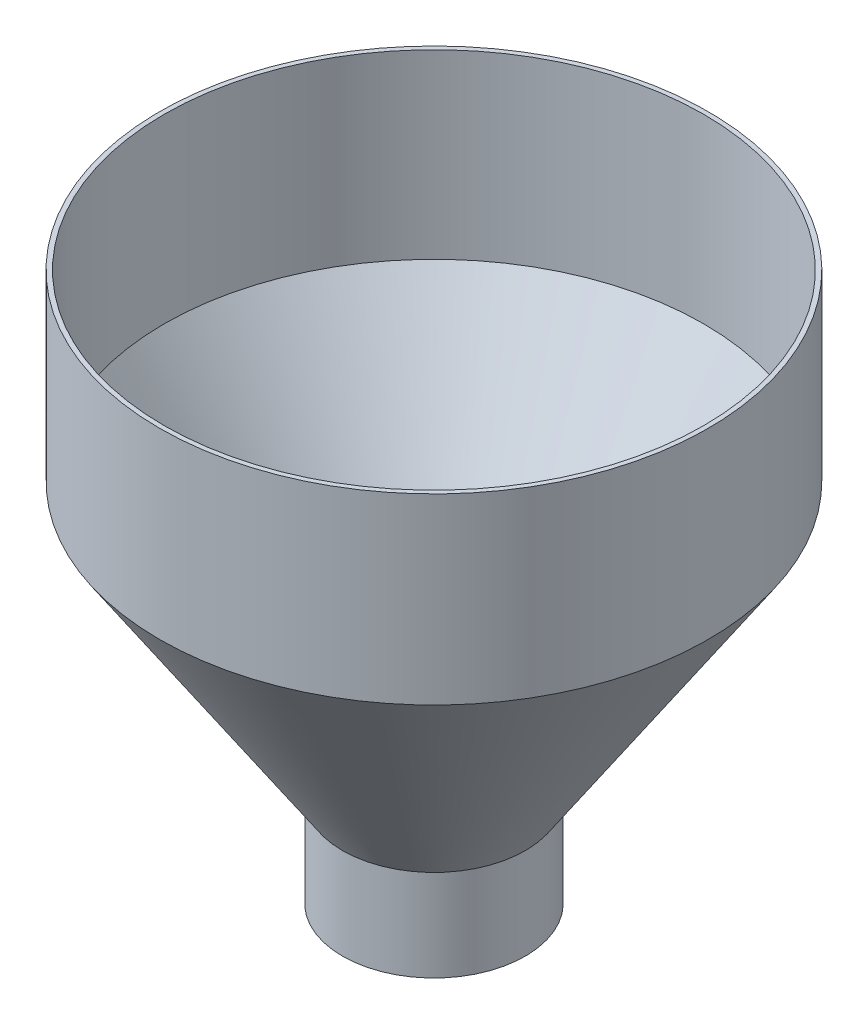
SolidWorks part; units mm, degrees
ref_plane "Front Plane" through (0, 0, 0) normal (0, 0, 1) x (1, 0, 0)
ref_plane "Top Plane" through (0, 0, 0) normal (0, 1, 0) x (1, 0, 0)
ref_plane "Right Plane" through (0, 0, 0) normal (1, 0, 0) x (0, 0, -1)
sketch "Sketch1" plane through (0, 0, 0) normal (0, 0, 1) x (1, 0, 0)
  line L0 (-120, 160) -> (-40, 40)
  line L1 (0, 0) -> (-120, 0)
  line L2 (0, 0) -> (0, 240)
  line L3 (0, 240) -> (-120, 240)
  line L4 (-120, 0) -> (-120, 240)
  line L5 (0, 0) -> (-40, 0)
  line L6 (0, 0) -> (0, 240)
  line L7 (0, 240) -> (-40, 240)
  line L8 (-40, 0) -> (-40, 240)
  line L9 (-120, 240) -> (0, 240)
  line L10 (-120, 240) -> (-120, 160)
  line L11 (-120, 160) -> (0, 160)
  line L12 (0, 240) -> (0, 160)
  line L13 (0, 0) -> (-40, 0)
  line L14 (0, 0) -> (0, 40)
  line L15 (0, 40) -> (-40, 40)
  line L16 (-40, 0) -> (-40, 40)
  line L17 (0, 249.8038) -> (0, -23.9483) construction
  dimension "D1" = 240
  dimension "D2" = 120
  dimension "D3" = 40
  dimension "D4" = 80
  dimension "D5" = 40
revolve "Revolve3" add sketch "Sketch1" angle 360 about L17
shell "Shell2" thickness 2
